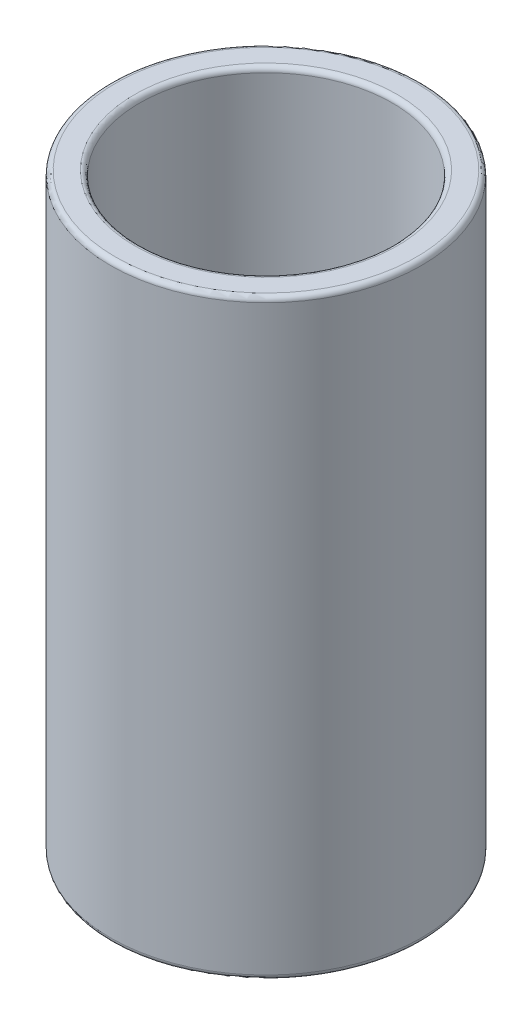
SolidWorks part; units mm, degrees
ref_plane "Front Plane" through (0, 0, 0) normal (0, 0, 1) x (1, 0, 0)
ref_plane "Top Plane" through (0, 0, 0) normal (0, 1, 0) x (1, 0, 0)
ref_plane "Right Plane" through (0, 0, 0) normal (1, 0, 0) x (0, 0, -1)
sketch "Sketch1" plane through (0, 0, 0) normal (0, 1, 0) x (1, 0, 0)
  circle A0 centre (0, 0) radius 31.5
  circle A1 centre (0, 0) radius 25.6
  dimension "D1" = 51.2
  dimension "D2" = 63
  dimension "D3" = 5.9
extrude "Boss-Extrude1" add sketch "Sketch1" along normal blind 120
fillet "Fillet1" radius 1 4 edges at (0, 0, 25.6) (0, 0, 31.5) (0, 120, 31.5) (0, 120, 25.6)
